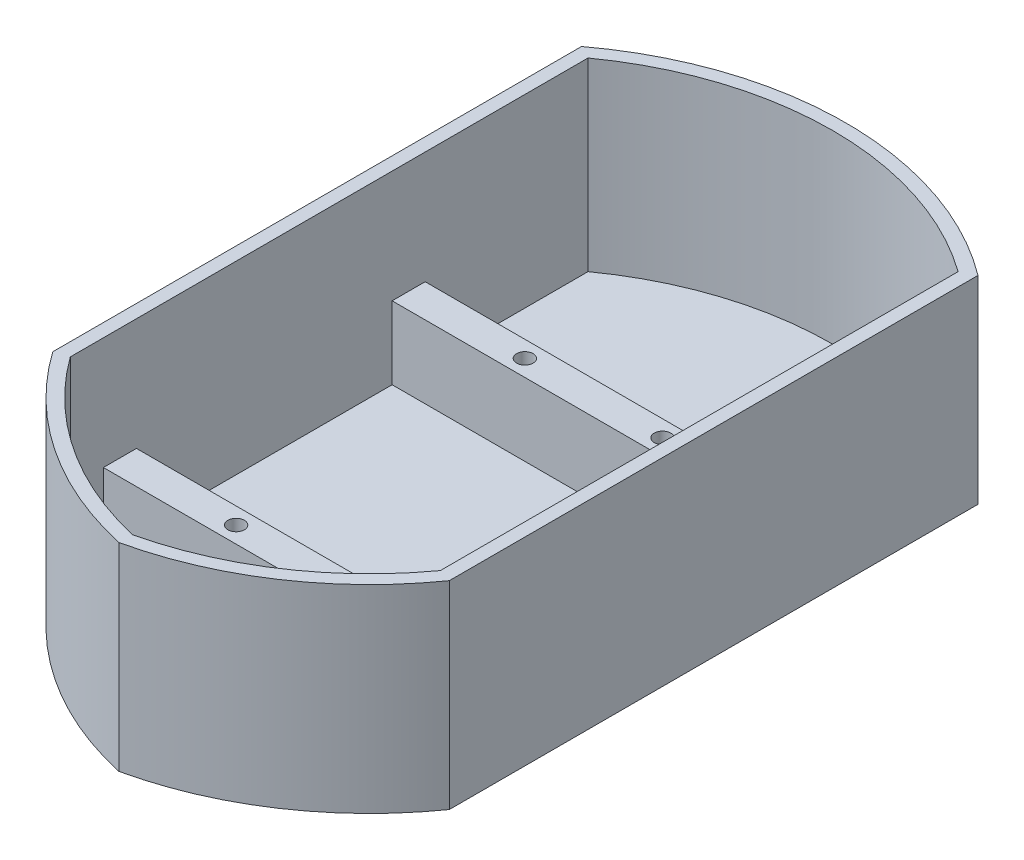
SolidWorks part; units mm, degrees
ref_plane "Alzado" through (0, 0, 0) normal (0, 0, 1) x (1, 0, 0)
ref_plane "Planta" through (0, 0, 0) normal (0, 1, 0) x (1, 0, 0)
ref_plane "Vista lateral" through (0, 0, 0) normal (1, 0, 0) x (0, 0, -1)
sketch "Croquis1" plane through (0, 0, 0) normal (0, 1, 0) x (1, 0, 0)
  line L0 (0, -55.2281) -> (0, 64.3245) construction
  line L1 (-30, 40) -> (-30, -40)
  line L2 (30, 40) -> (30, -40)
  line L3 (-30, 40) -> (30, -40) construction
  line L4 (30, 40) -> (-30, -40) construction
  arc A0 (-30, -40) -> (0, -60) centre (10.8695, -11.1958) ccw
  arc A1 (30, 40) -> (0, 50) centre (0, 0) ccw
  arc A2 (0, -60) -> (30, -40) centre (-10.8695, -11.1958) ccw
  arc A3 (-30, 40) -> (0, 50) centre (0, 0) cw
  point P12 (0, 0)
  dimension "D2" = 50
  dimension "D3" = 50
  dimension "D1" = 30
  dimension "D4" = 60
extrude "Saliente-Extruir1" add sketch "Croquis1" along normal blind 30
shell "Vaciado1" thickness 2
sketch "Croquis2" plane through (0, 2, 0) normal (0, 1, 0) x (1, 0, 0)
  line L0 (0, 0) -> (0, -20.3372) construction
  line L1 (10.415, -10) -> (-10.415, -10) construction
  line L2 (10.415, 11.845) -> (-10.415, 11.845) construction
  line L3 (10.415, 11.845) -> (10.415, -31.845) construction
  line L4 (10.415, -31.845) -> (-10.415, -31.845) construction
  line L5 (-10.415, 11.845) -> (-10.415, -31.845) construction
  line L6 (-28, 38.9872) -> (-28, -39.3589) construction
  line L7 (28, -34.345) -> (-28, -34.345)
  line L8 (28, -34.345) -> (28, -29.345)
  line L9 (28, -29.345) -> (-28, -29.345)
  line L10 (-28, -34.345) -> (-28, -29.345)
  line L11 (28, -39.3589) -> (28, 38.9872) construction
  line L12 (28, 14.345) -> (28, 9.345)
  line L13 (28, 9.345) -> (-28, 9.345)
  line L14 (28, 14.345) -> (-28, 14.345)
  line L15 (-28, 14.345) -> (-28, 9.345)
  circle A0 centre (-10.415, -31.845) radius 1.25
  circle A1 centre (10.415, -31.845) radius 1.25
  circle A2 centre (-10.415, 11.845) radius 1.25
  circle A3 centre (10.415, 11.845) radius 1.25
  point P1 (0, 0)
  point P2 (0, -31.845)
  point P11 (0, -10)
  point P16 (-28, -31.845)
  dimension "D5" = 2.5
  dimension "D1" = 43.69
  dimension "D2" = 20.83
  dimension "D3" = 10
  dimension "D4" = 5
extrude "Saliente-Extruir2" add sketch "Croquis2" along normal blind 11
